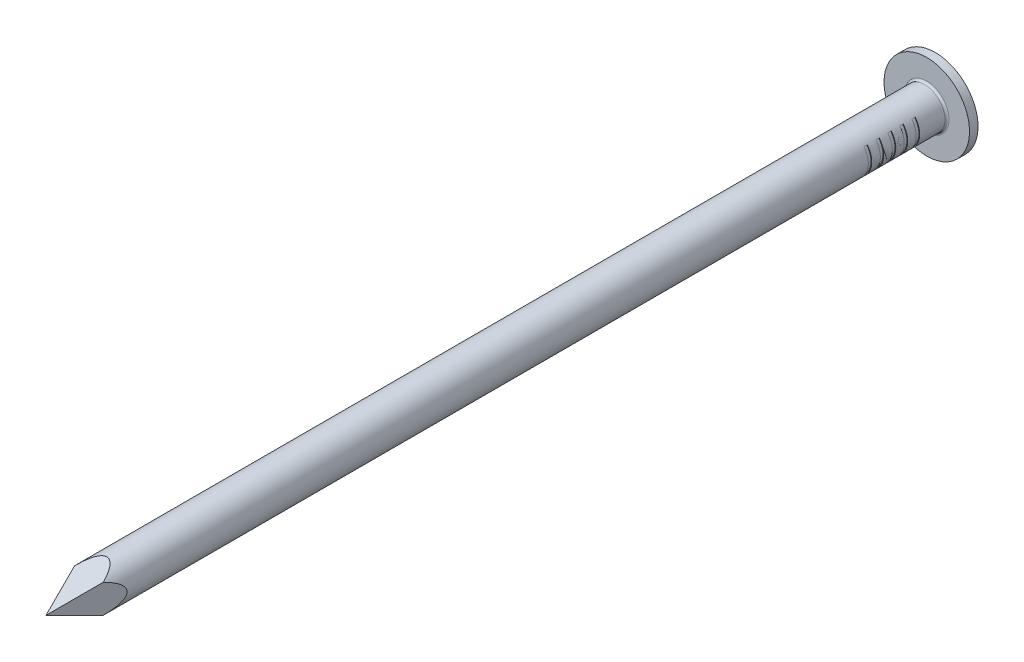
SolidWorks part; units mm, degrees
ref_plane "Front Plane" through (0, 0, 0) normal (0, 0, 1) x (1, 0, 0)
ref_plane "Top Plane" through (0, 0, 0) normal (0, 1, 0) x (1, 0, 0)
ref_plane "Right Plane" through (0, 0, 0) normal (1, 0, 0) x (0, 0, -1)
sketch "Sketch1" plane through (0, 0, 0) normal (1, 0, 0) x (0, 0, -1)
  line L0 (-41.275, 0) -> (41.275, 0) construction
  line L1 (-41.275, 1.8796) -> (-41.275, -1.8796) construction
  line L2 (41.275, -3.9688) -> (41.275, 3.9688) construction
  point P4 (0, 0)
  point P8 (-41.275, 0)
  point P11 (41.275, 0)
  dimension "Length" = 82.55
  dimension "Shank Diameter" = 3.7592
  dimension "Head Diameter" = 7.9375
sketch "Sketch2" plane through (0, 0, 0) normal (1, 0, 0) x (0, 0, -1)
  line L1 (-35.6362, -1.8796) -> (41.275, -1.8796)
  line L2 (-41.275, 0) -> (41.275, 0) construction
  line L3 (-41.275, 0) -> (41.275, 0)
  line L4 (41.275, 0) -> (41.275, -1.8796)
  line L5 (-41.275, 0) -> (-41.275, -1.8796)
  line L7 (-41.275, -1.8796) -> (-35.6362, -1.8796)
  line L8 (-35.6362, -1.8796) -> (-41.275, -0.0025) construction
  line L9 (41.275, -3.9688) -> (41.275, 3.9688) construction
  point P2 (33.3375, 0)
  dimension "D1" = 5.6388
  dimension "D2" = 0.0025
  dimension "D3" = 7.9375
revolve "Revolve1" add sketch "Sketch2" angle 360 about L3
sketch "Sketch3" plane through (0, 0, 0) normal (1, 0, 0) x (0, 0, -1)
  line L0 (-41.275, -0.0025) -> (-35.6362, -1.8796)
  line L1 (-35.6362, -1.8796) -> (-41.275, -1.8796)
  line L2 (-41.275, -1.8796) -> (-41.275, -0.0025)
  line L3 (-41.275, 0) -> (41.275, 0) construction
  line L4 (-41.275, 0) -> (41.275, 0) construction
extrude "Cut-Extrude1" cut sketch "Sketch3" against normal through all both and the other way through all
pattern_circular "CirPattern1" count 4 over 360 about axis through (0, 0, 0) along (0, 0, 1) of "Cut-Extrude1"
sketch "Sketch5" plane through (0, 0, 0) normal (1, 0, 0) x (0, 0, -1)
  line L0 (41.275, -3.9688) -> (41.275, 3.9688) construction
  line L1 (41.275, 0) -> (41.275, 3.9688)
  line L2 (40.4812, 3.9688) -> (40.4812, 0)
  line L3 (-41.275, 0) -> (41.275, 0) construction
  line L5 (40.4812, 3.9688) -> (41.275, 3.9688)
  line L6 (41.275, 0) -> (0, 0) construction
  line L7 (40.4812, 0) -> (41.275, 0)
  point P2 (32.0675, 0)
  point P3 (-40.005, 0)
  point P12 (40.4812, 3.9688)
  dimension "D1" = 0.7937
  dimension "D2" = 1.27
  dimension "D4" = 72.0725
  dimension "D3" = 1.27
revolve "Revolve2" add sketch "Sketch5" angle 360 about L6
fillet "Fillet1" radius 0.188 1 edges at (1.8796, 0, -40.4813)
ref_plane "Plane1" through (1.8796, 0, 0) normal (1, 0, 0) x (0, 0, -1)
sketch "Sketch6" plane through (1.8796, 0, 0) normal (1, 0, 0) x (0, 0, -1)
  line L0 (-41.275, 0) -> (41.275, 0) construction
  line L1 (-41.275, 0) -> (41.275, 0) construction
  line L3 (33.1788, -1.1748) -> (33.4962, -1.1748)
  line L4 (33.1788, -1.1748) -> (33.1788, 1.1747)
  line L5 (33.1788, 1.1747) -> (33.4962, 1.1747)
  line L6 (33.4962, -1.1748) -> (33.4962, 1.1747)
  line L7 (33.1788, -1.1748) -> (33.4962, 1.1747) construction
  line L8 (33.1788, 1.1747) -> (33.4962, -1.1748) construction
  line L24 (34.29, -1.1748) -> (34.6075, -1.1748)
  line L25 (34.6075, -1.1748) -> (34.6075, 1.1747)
  line L26 (34.29, -1.1748) -> (34.29, 1.1747)
  line L27 (34.29, 1.1747) -> (34.6075, 1.1747)
  line L28 (35.4013, -1.1748) -> (35.7188, -1.1748)
  line L29 (35.7188, -1.1748) -> (35.7188, 1.1747)
  line L30 (35.4013, -1.1748) -> (35.4013, 1.1747)
  line L31 (35.4013, 1.1747) -> (35.7188, 1.1747)
  line L32 (36.5125, -1.1748) -> (36.83, -1.1748)
  line L33 (36.83, -1.1748) -> (36.83, 1.1747)
  line L34 (36.5125, -1.1748) -> (36.5125, 1.1747)
  line L35 (36.5125, 1.1747) -> (36.83, 1.1747)
  line L36 (37.6238, -1.1748) -> (37.9413, -1.1748)
  line L37 (37.9413, -1.1748) -> (37.9413, 1.1747)
  line L38 (37.6238, -1.1748) -> (37.6238, 1.1747)
  line L39 (37.6238, 1.1747) -> (37.9413, 1.1747)
  point P2 (33.3375, 0)
  dimension "D2" = 0.3175
  dimension "D3" = 2.3495
  dimension "D4" = 1.1113
  dimension "D1" = 5
extrude "Cut-Extrude3" cut sketch "Sketch6" against normal offset from surface (0.4946 mm away) 0.0635
mirror "Mirror1" about plane through (0, 0, 0) normal (1, 0, 0) of "Cut-Extrude3"
equation "\"D1@Sketch2\"=\"Shank Diameter@Sketch1\"*1.5"
equation "\"D1@Sketch5\" = \"Head Diameter@Sketch1\" * 0.1"
equation "\"D3@Sketch6\"=\"Shank Diameter@Sketch1\"*0.625"
equation "\"D4@Sketch6\"=\"D2@Sketch6\"*3.5"
equation "\"D1@Fillet1\"=\"Shank Diameter@Sketch1\"*0.05"
